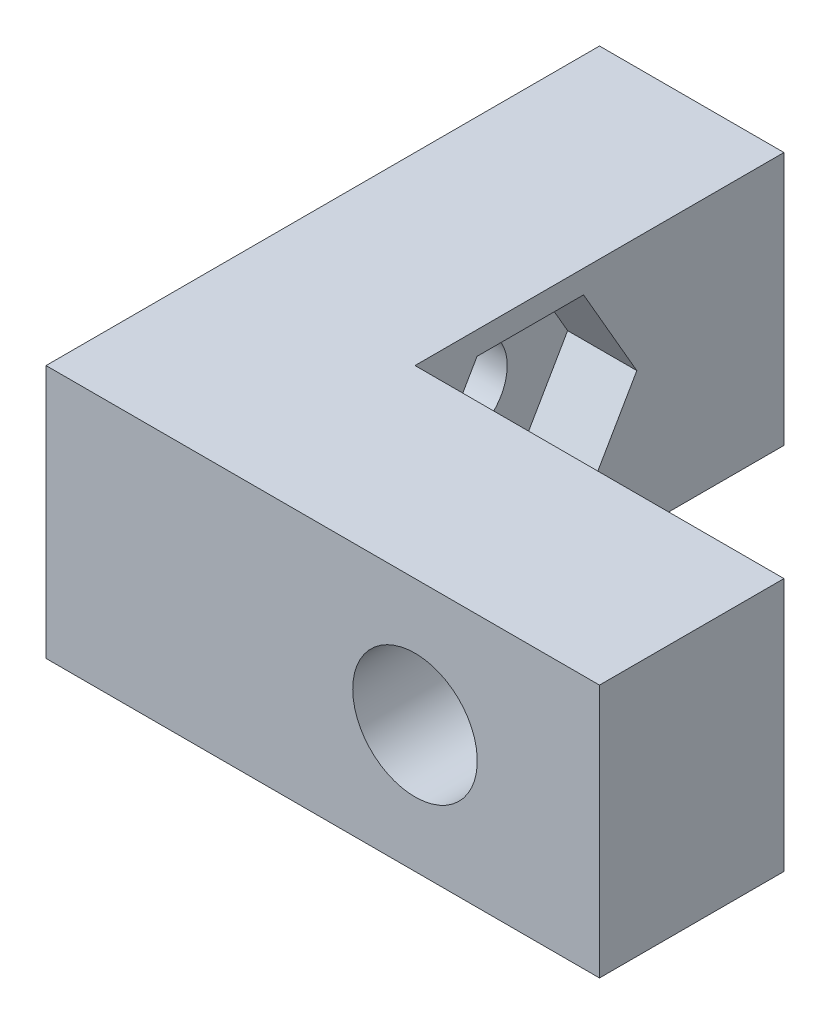
SolidWorks part; units mm, degrees
ref_plane "前视基准面" through (0, 0, 0) normal (0, 0, 1) x (1, 0, 0)
ref_plane "上视基准面" through (0, 0, 0) normal (0, 1, 0) x (1, 0, 0)
ref_plane "右视基准面" through (0, 0, 0) normal (1, 0, 0) x (0, 0, -1)
sketch "草图1" plane through (0, 0, 0) normal (0, 1, 0) x (1, 0, 0)
  line L0 (0, 0) -> (12, 0)
  line L1 (12, 0) -> (12, 4)
  line L2 (12, 4) -> (4, 4)
  line L3 (4, 4) -> (4, 12)
  line L4 (4, 12) -> (0, 12)
  line L5 (0, 12) -> (0, 0)
  dimension "D1" = 4
  dimension "D2" = 12
  dimension "D3" = 12
  dimension "D4" = 4
extrude "凸台-拉伸1" add sketch "草图1" along normal blind 5.5
sketch "草图2" plane through (0, 0, 0) normal (-1, 0, 0) x (0, 0, 1)
  line L0 (0, 2.75) -> (-6.5, 2.75) construction
  line L1 (0, 5.5) -> (0, 0) construction
  line L2 (-6.5, 2.75) -> (-6.5, 3) construction
  line L3 (-12, 5.5) -> (0, 5.5) construction
  circle A0 centre (-6.5, 3) radius 1
  dimension "D1" = 2
  dimension "D2" = 6.5
  dimension "D3" = 2.5
extrude "切除-拉伸1" cut sketch "草图2" against normal up to next
sketch "草图3" plane through (4, 0, 0) normal (1, 0, 0) x (0, 0, -1)
  line L1 (8.8094, 3) -> (7.6547, 5)
  line L2 (7.6547, 5) -> (5.3453, 5)
  line L3 (5.3453, 5) -> (4.1906, 3)
  line L4 (4.1906, 3) -> (5.3453, 1)
  line L5 (5.3453, 1) -> (7.6547, 1)
  line L6 (7.6547, 1) -> (8.8094, 3)
  circle A0 centre (6.5, 3) radius 2 construction
  dimension "D1" = 4
extrude "切除-拉伸2" cut sketch "草图3" against normal blind 1.5
sketch "草图4" plane through (0, 0, -4) normal (0, 0, -1) x (-1, 0, 0)
  line L0 (-8, 5.5) -> (-8, 0) construction
  line L1 (-12, 5.5) -> (-4, 5.5) construction
  line L2 (-12, 0) -> (-4, 0) construction
  circle A0 centre (-8, 2.75) radius 1.35
  dimension "D1" = 2.7
extrude "切除-拉伸3" cut sketch "草图4" against normal up to next
